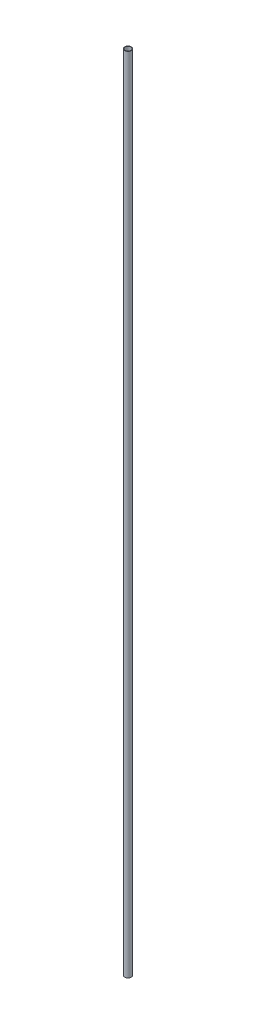
SolidWorks part; units mm, degrees
ref_plane "Front Plane" through (0, 0, 0) normal (0, 0, 1) x (1, 0, 0)
ref_plane "Top Plane" through (0, 0, 0) normal (0, 1, 0) x (1, 0, 0)
ref_plane "Right Plane" through (0, 0, 0) normal (1, 0, 0) x (0, 0, -1)
sketch "Sketch1" plane through (0, 0, 0) normal (0, 1, 0) x (1, 0, 0)
  circle A0 centre (0, 0) radius 4
  circle A1 centre (0, 0) radius 3.5
  dimension "D1" = 8
  dimension "D2" = 7
extrude "Boss-Extrude1" add sketch "Sketch1" along normal blind 970
